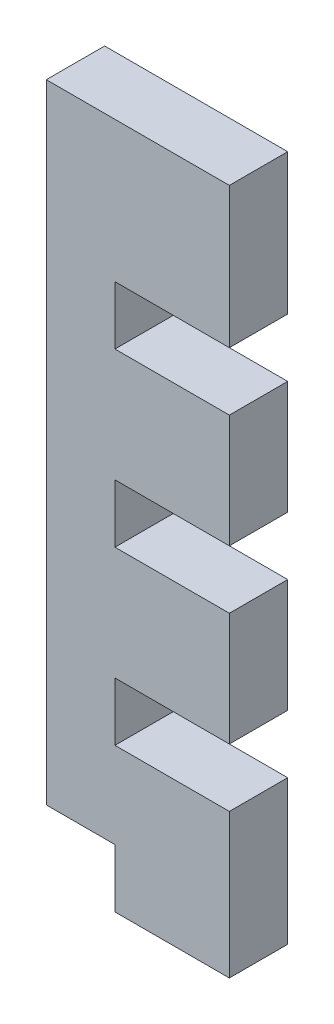
SolidWorks part; units mm, degrees
ref_plane "Front Plane" through (0, 0, 0) normal (0, 0, 1) x (1, 0, 0)
ref_plane "Top Plane" through (0, 0, 0) normal (0, 1, 0) x (1, 0, 0)
ref_plane "Right Plane" through (0, 0, 0) normal (1, 0, 0) x (0, 0, -1)
sketch "Sketch1" plane through (0, 0, 0) normal (0, 0, 1) x (1, 0, 0)
  line L0 (-8, -24.9) -> (-2, -24.9)
  line L1 (8, -30) -> (-2, -30)
  line L2 (8, -30) -> (8, -17.3883)
  line L3 (8, 30) -> (-8, 30)
  line L4 (-8, -24.9) -> (-8, 30)
  line L5 (8, -30) -> (-8, 30) construction
  line L6 (8, 30) -> (-6.64, -24.9) construction
  line L7 (-2, -24.9) -> (-2, -30)
  line L8 (8, -12.2883) -> (8, -2.3883)
  line L9 (8, -17.3883) -> (-2, -17.3883)
  line L11 (8, -12.2883) -> (-2, -12.2883)
  line L12 (-2, -17.3883) -> (-2, -12.2883)
  line L13 (8, 2.7117) -> (-2, 2.7117)
  line L14 (-2, -2.3883) -> (-2, 2.7117)
  line L15 (8, -2.3883) -> (-2, -2.3883)
  line L16 (8, 17.7117) -> (-2, 17.7117)
  line L17 (-2, 12.6117) -> (-2, 17.7117)
  line L18 (8, 12.6117) -> (-2, 12.6117)
  line L19 (8, 2.7117) -> (8, 12.6117)
  line L20 (8, 17.7117) -> (8, 30)
  point P0 (0, 0)
  dimension "D1" = 16
  dimension "D2" = 60
  dimension "D3" = 5.1
  dimension "D4" = 6
  dimension "D5" = 5.1
  dimension "D6" = 10
  dimension "D7" = 3
extrude "Boss-Extrude1" add sketch "Sketch1" along normal blind 5.1
